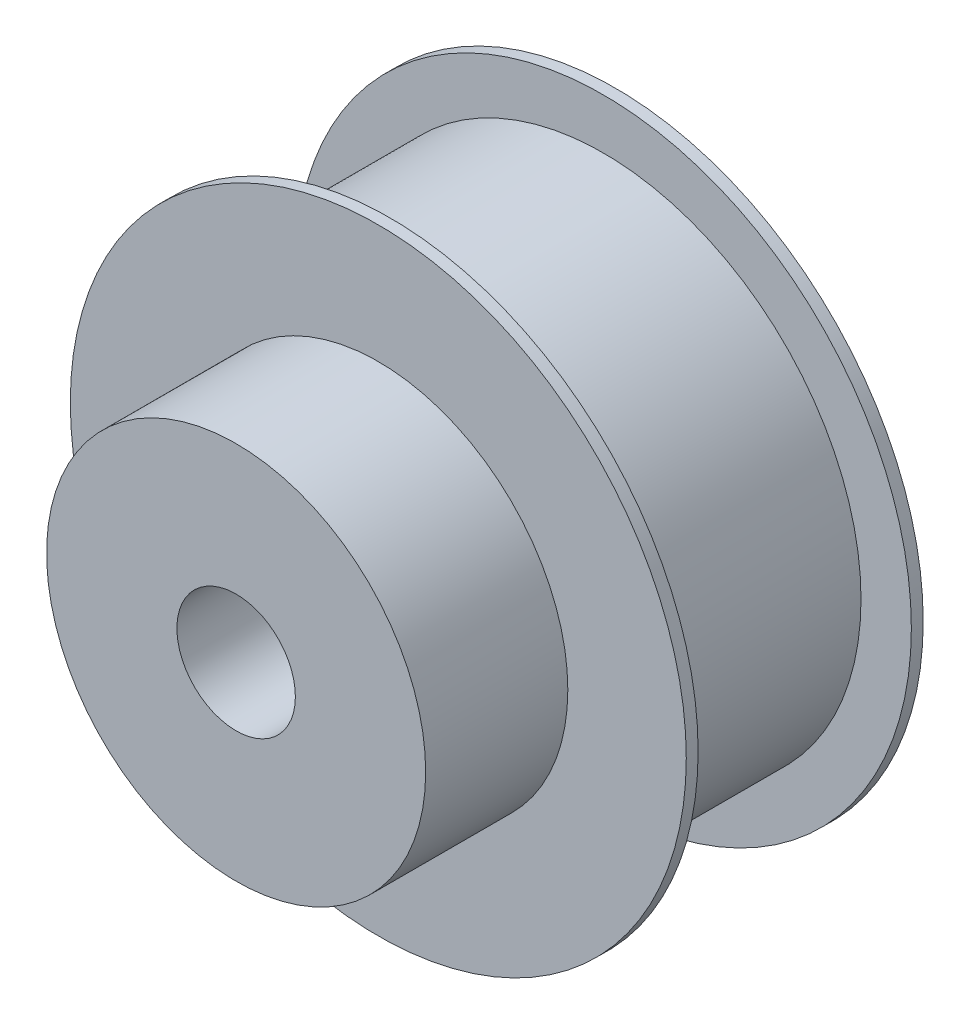
SolidWorks part; units mm, degrees
ref_plane "Plan de face" through (0, 0, 0) normal (0, 0, 1) x (1, 0, 0)
ref_plane "Plan de dessus" through (0, 0, 0) normal (0, 1, 0) x (1, 0, 0)
ref_plane "Plan de droite" through (0, 0, 0) normal (1, 0, 0) x (0, 0, -1)
sketch "Esquisse1" plane through (0, 0, 0) normal (0, 0, 1) x (1, 0, 0)
  circle A1 centre (0, 0) radius 13
extrude "Extrusion1" add sketch "Esquisse1" along normal blind 0.5
sketch "Esquisse2" plane through (0, 0, 0.5) normal (0, 0, 1) x (1, 0, 0)
  circle A0 centre (0, 0) radius 10.875
extrude "Extrusion2" add sketch "Esquisse2" along normal blind 9
sketch "Esquisse3" plane through (0, 0, 9.5) normal (0, 0, 1) x (1, 0, 0)
  circle A0 centre (0, 0) radius 13
extrude "Extrusion3" add sketch "Esquisse3" along normal blind 0.5
sketch "Esquisse4" plane through (0, 0, 10) normal (0, 0, 1) x (1, 0, 0)
  circle A0 centre (0, 0) radius 8
extrude "Extrusion4" add sketch "Esquisse4" along normal blind 6
sketch "Esquisse5" plane through (0, 0, 16) normal (0, 0, 1) x (1, 0, 0)
  circle A0 centre (0, 0) radius 2.5
extrude "Extrusion5" cut sketch "Esquisse5" against normal through all
